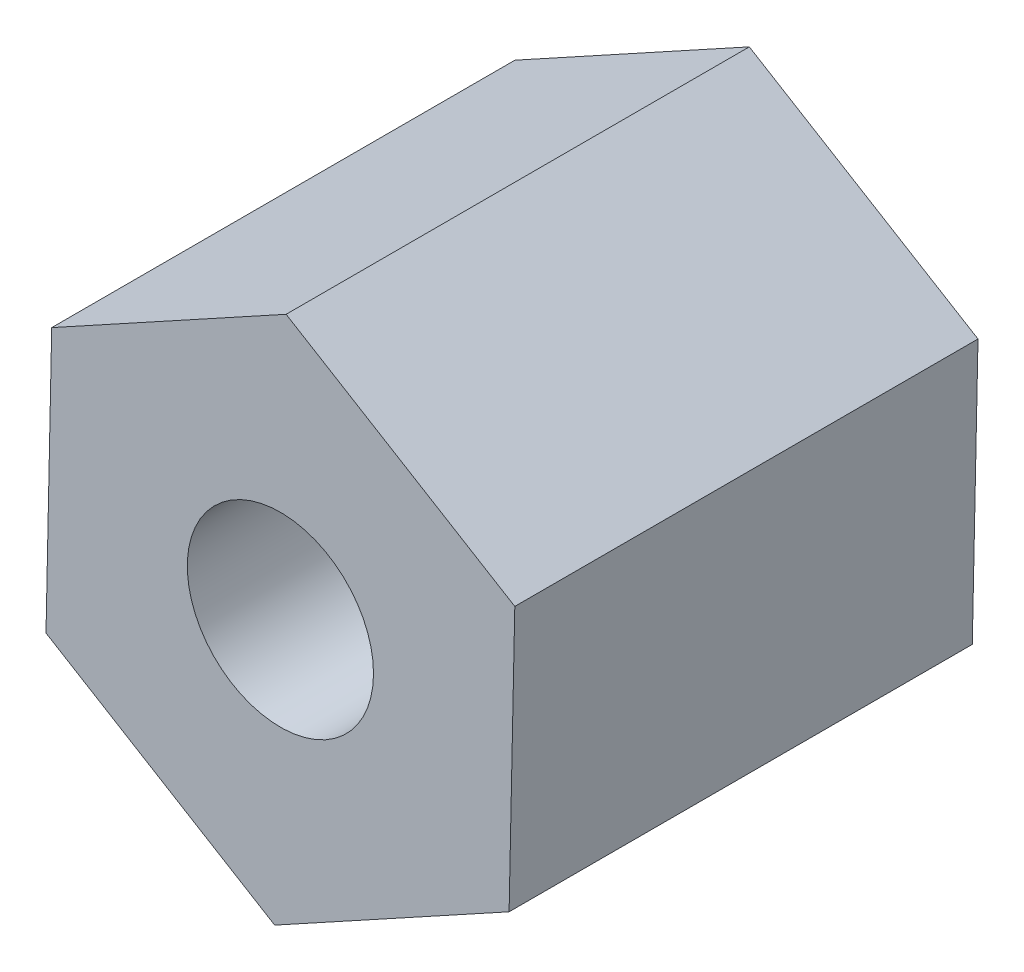
SolidWorks part; units mm, degrees
material "Stainless Steel (ferritic)"
ref_plane "Front Plane" through (0, 0, 0) normal (0, 0, 1) x (1, 0, 0)
ref_plane "Top Plane" through (0, 0, 0) normal (0, 1, 0) x (1, 0, 0)
ref_plane "Right Plane" through (0, 0, 0) normal (1, 0, 0) x (0, 0, -1)
sketch "Thickness" plane through (0, 0, 0) normal (1, 0, 0) x (0, 0, -1)
  line L0 (0, 0) -> (-12.7, 0)
  dimension "D1" = 12.7
sketch "Sketch1" plane through (0, 0, 0) normal (0, 0, 1) x (1, 0, 0)
  line L1 (6.2702, -3.801) -> (6.4269, 3.5297)
  line L2 (6.4269, 3.5297) -> (0.1566, 7.3307)
  line L3 (0.1566, 7.3307) -> (-6.2702, 3.801)
  line L4 (-6.2702, 3.801) -> (-6.4269, -3.5297)
  line L5 (-6.4269, -3.5297) -> (-0.1566, -7.3307)
  line L6 (-0.1566, -7.3307) -> (6.2702, -3.801)
  circle A0 centre (0, 0) radius 6.35 construction
  dimension "D1" = 12.7
extrude "Boss-Extrude1" add sketch "Sketch1" along normal up to vertex (12.7 mm away) up to point (0, 0, 12.7)
hole_wizard "Tap Drill for 1/4-20 Tap1" positions "Sketch4" profile "Sketch3" hole size "1/4-20" standard "ANSI Inch" end condition through all
sketch "Sketch4" plane through (0, 0, 12.7) normal (0, 0, 1) x (1, 0, 0)
  point P0 (0, 0)
sketch "Sketch3" plane through (0, 0, 12.7) normal (1, 0, 0) x (0, -1, 0)
  line L0 (0, 0) -> (0, 12.7)
  line L1 (0, 12.7) -> (2.5527, 12.7)
  line L2 (2.5527, 12.7) -> (2.5527, 0)
  line L5 (2.5527, 0) -> (0, 0)
  line L11 (0, -6.35) -> (0, 107.95) construction
  dimension "Thru Hole Dia." = 5.1054
  dimension "Thru Hole Depth" = 12.7
